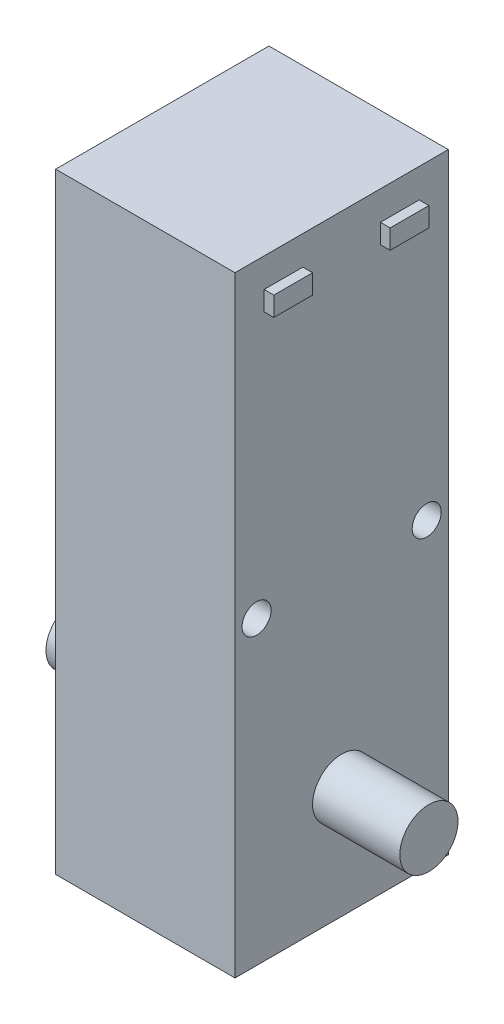
SolidWorks part; units mm, degrees
ref_plane "Plan de face" through (0, 0, 0) normal (0, 0, 1) x (1, 0, 0)
ref_plane "Plan de dessus" through (0, 0, 0) normal (0, 1, 0) x (1, 0, 0)
ref_plane "Plan de droite" through (0, 0, 0) normal (1, 0, 0) x (0, 0, -1)
sketch "Esquisse1" plane through (0, 0, 0) normal (1, 0, 0) x (0, 0, -1)
  line L0 (11, 0) -> (11, 63) construction
  line L1 (0, 0) -> (22, 0)
  line L2 (0, 0) -> (0, 63)
  line L3 (0, 63) -> (22, 63)
  line L4 (22, 0) -> (22, 63)
  circle A0 centre (2.225, 31) radius 1.5
  circle A1 centre (19.775, 31) radius 1.5
  dimension "D3" = 3
  dimension "D1" = 22
  dimension "D2" = 63
  dimension "D4" = 17.55
  dimension "D5" = 31
extrude "Boss.-Extru.1" add sketch "Esquisse1" along normal blind 18.5
sketch "Esquisse2" plane through (18.5, 0, 0) normal (1, 0, 0) x (0, 0, -1)
  line L0 (11, 63) -> (11, 0) construction
  line L1 (22, 63) -> (0, 63) construction
  line L2 (0, 0) -> (22, 0) construction
  circle A0 centre (11, 11.5) radius 3
  dimension "D1" = 6
  dimension "D2" = 11.5
extrude "Boss.-Extru.2" add sketch "Esquisse2" along normal blind 9 and the other way blind 27.5
sketch "Esquisse3" plane through (18.5, 0, 0) normal (1, 0, 0) x (0, 0, -1)
  line L0 (11, 63) -> (11, 0) construction
  line L1 (22, 63) -> (0, 63) construction
  line L2 (0, 0) -> (22, 0) construction
  line L3 (22, 0) -> (22, 63) construction
  line L4 (3, 60) -> (7, 60)
  line L5 (3, 60) -> (3, 58)
  line L6 (3, 58) -> (7, 58)
  line L7 (7, 60) -> (7, 58)
  line L8 (19, 58) -> (15, 58)
  line L9 (15, 60) -> (15, 58)
  line L10 (19, 60) -> (15, 60)
  line L11 (19, 60) -> (19, 58)
  dimension "D1" = 3
  dimension "D2" = 2
  dimension "D3" = 4
  dimension "D4" = 15
extrude "Boss.-Extru.3" add sketch "Esquisse3" along normal blind 1
